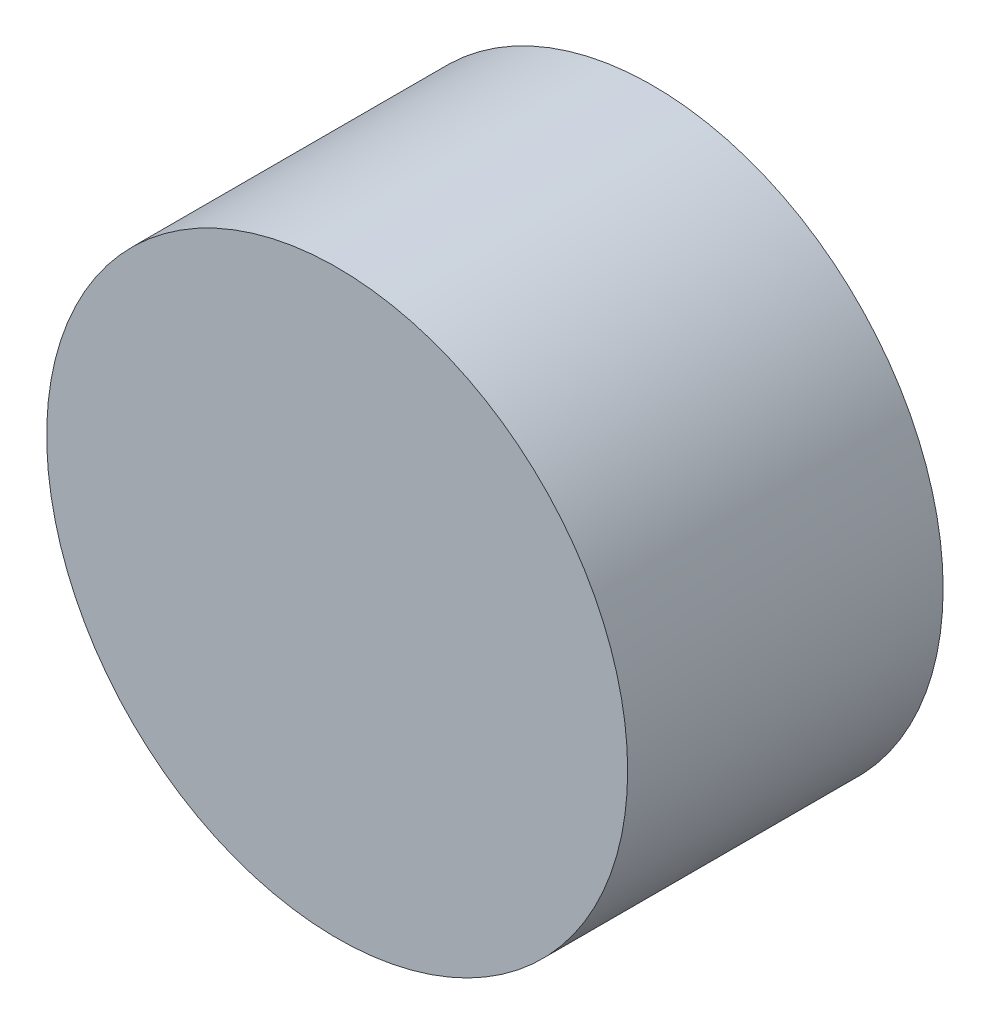
SolidWorks part; units mm, degrees
ref_plane "Front" through (0, 0, 0) normal (0, 0, 1) x (1, 0, 0)
ref_plane "Top" through (0, 0, 0) normal (0, 1, 0) x (1, 0, 0)
ref_plane "Right" through (0, 0, 0) normal (1, 0, 0) x (0, 0, -1)
sketch "Sketch1" plane through (0, 0, 0) normal (0, 0, 1) x (1, 0, 0)
  circle A0 centre (0, 0) radius 50.8
  dimension "D1" = 101.6
extrude "Boss-Extrude1" add sketch "Sketch1" along normal blind 55.1688
ref_plane "Plane1" through (0, 50.8, 0) normal (0, -1, 0) x (-1, 0, 0)
